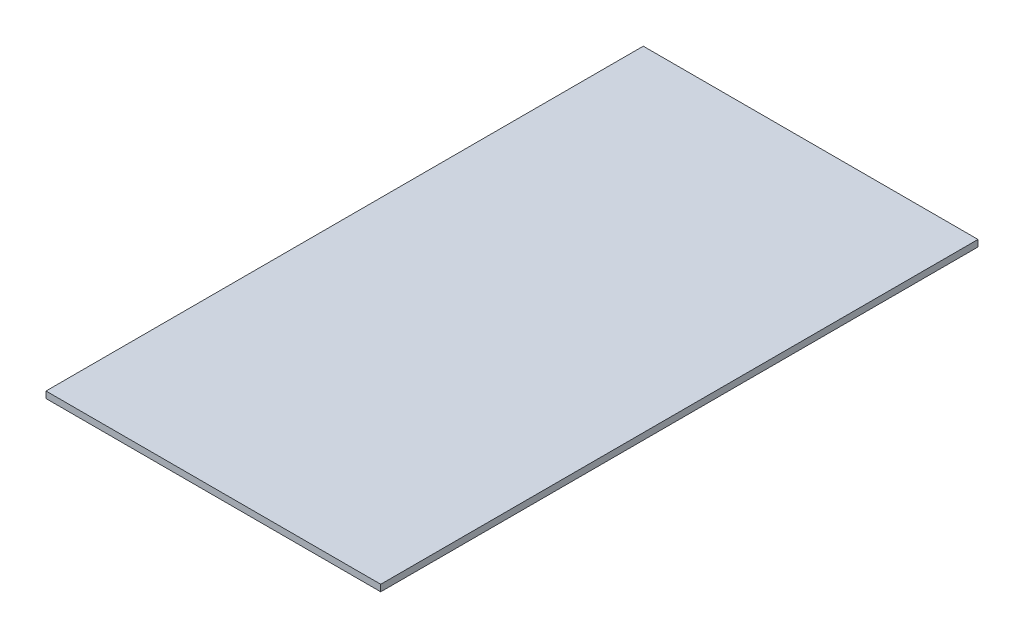
SolidWorks part; units mm, degrees
ref_plane "Front Plane" through (0, 0, 0) normal (0, 0, 1) x (1, 0, 0)
ref_plane "Top Plane" through (0, 0, 0) normal (0, 1, 0) x (1, 0, 0)
ref_plane "Right Plane" through (0, 0, 0) normal (1, 0, 0) x (0, 0, -1)
sketch "Sketch2" plane through (0, 385.8619, 0) normal (0, 1, 0) x (1, 0, 0)
  line L8 (-48.1672, -6.685) -> (206.8328, -6.685)
  line L9 (206.8328, -6.685) -> (206.8328, 448.315)
  line L10 (-48.1672, 448.315) -> (-48.1672, -6.685)
  line L11 (206.8328, 448.315) -> (-48.1672, 448.315)
  line L12 (-48.1672, -6.685) -> (206.8328, -6.685)
  line L13 (206.8328, -6.685) -> (206.8328, 448.315)
  line L14 (-48.1672, 448.315) -> (-48.1672, -6.685)
  line L15 (206.8328, 448.315) -> (-48.1672, 448.315)
  dimension "D1" = 2.5
extrude "Boss-Extrude1" add sketch "Sketch2" against normal blind 5
